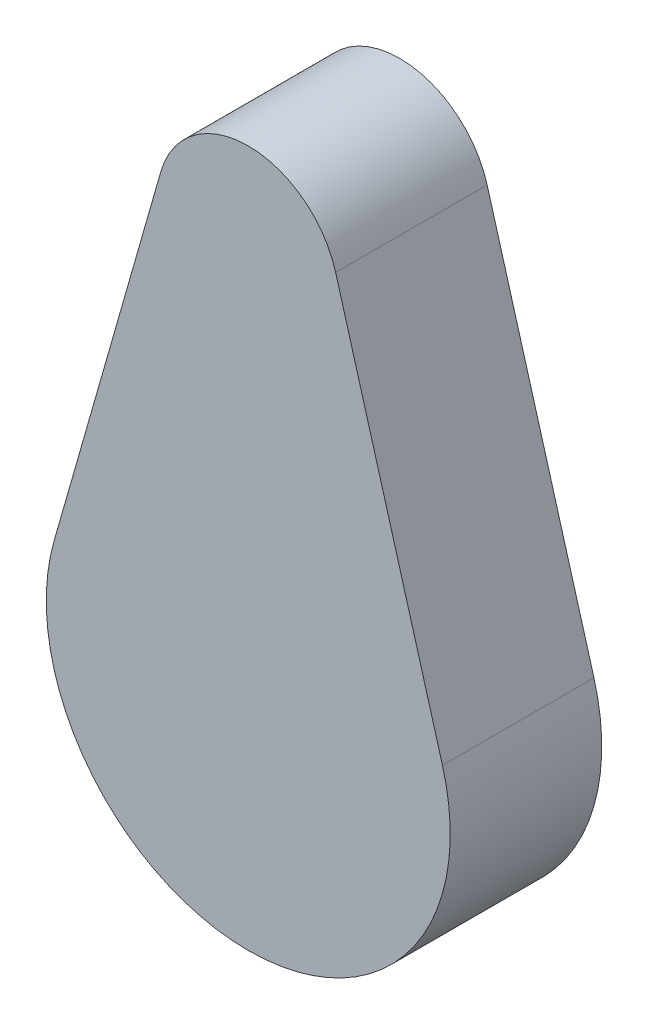
SolidWorks part; units mm, degrees
ref_plane "Alzado" through (0, 0, 0) normal (0, 0, 1) x (1, 0, 0)
ref_plane "Planta" through (0, 0, 0) normal (0, 1, 0) x (1, 0, 0)
ref_plane "Vista lateral" through (0, 0, 0) normal (1, 0, 0) x (0, 0, -1)
sketch "Croquis1" plane through (0, 0, 0) normal (0, 0, 1) x (1, 0, 0)
  line L0 (-17.306, 4.95) -> (-38.4578, -69)
  line L1 (0, -80) -> (0, -73.4745) construction
  line L2 (17.306, 4.95) -> (38.4578, -69)
  arc A0 (17.306, 4.95) -> (-17.306, 4.95) centre (0, 0) ccw
  arc A1 (-38.4578, -69) -> (38.4578, -69) centre (0, -80) ccw
  point P8 (17.7158, 3.1858)
  dimension "D2" = 80
  dimension "D3" = 36
  dimension "D1" = 80
extrude "Saliente-Extruir2" add sketch "Croquis1" along normal mid plane 30
sketch "Croquis2" plane through (0, 0, -15) normal (0, 0, -1) x (-1, 0, 0)
  circle A0 centre (0, -80) radius 12
  dimension "D1" = 24
extrude "Saliente-Extruir3" add sketch "Croquis2" along normal blind 12
